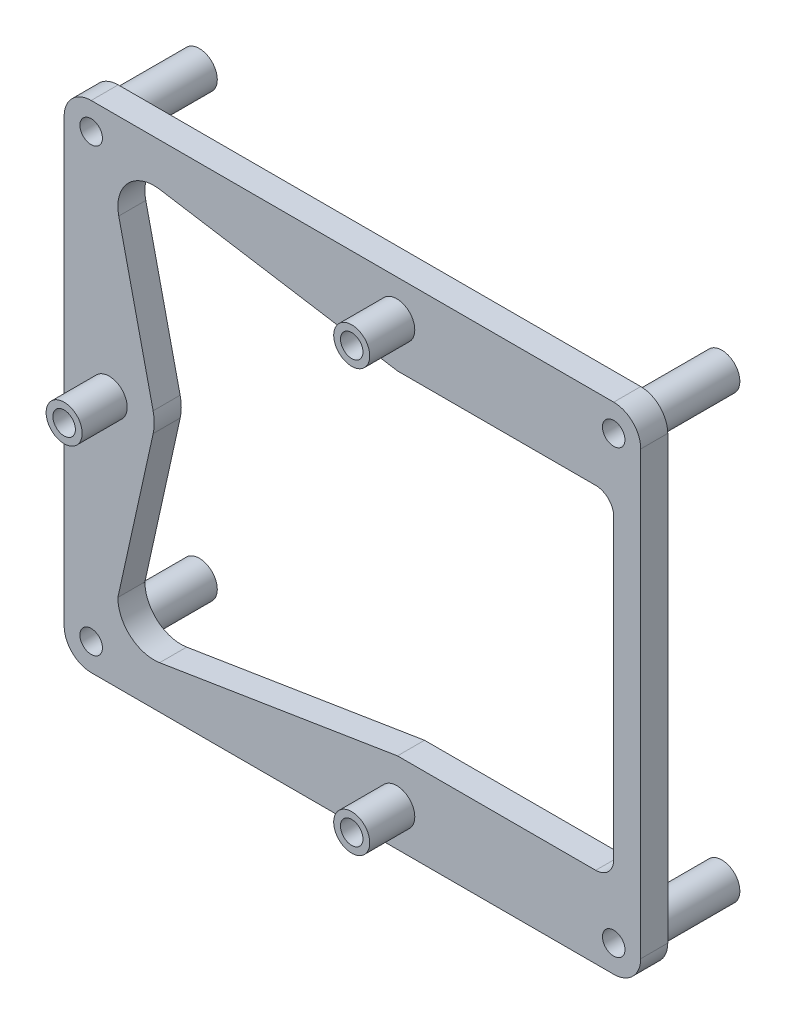
SolidWorks part; units mm, degrees
ref_plane "Alzado" through (0, 0, 0) normal (0, 0, 1) x (1, 0, 0)
ref_plane "Planta" through (0, 0, 0) normal (0, 1, 0) x (1, 0, 0)
ref_plane "Vista lateral" through (0, 0, 0) normal (1, 0, 0) x (0, 0, -1)
sketch "Croquis1" plane through (0, 0, 0) normal (0, 0, 1) x (1, 0, 0)
  line L1 (-36.2308, 25.8462) -> (21.7692, 25.8462)
  line L2 (-39.2308, 22.8462) -> (-39.2308, -26.1538)
  line L3 (-36.2308, -29.1538) -> (21.7692, -29.1538)
  line L4 (24.7692, 22.8462) -> (24.7692, -26.5057)
  arc A4 (-36.2308, 25.8462) -> (-39.2308, 22.8462) centre (-36.2308, 22.8462) ccw
  arc A5 (24.7692, 22.8462) -> (21.7692, 25.8462) centre (21.7692, 22.8462) ccw
  arc A6 (21.7692, -29.1538) -> (24.7692, -26.1538) centre (21.7692, -26.1538) ccw
  arc A7 (-39.2308, -26.1538) -> (-36.2308, -29.1538) centre (-36.2308, -26.1538) ccw
  arc A8 (-36.2308, 25.8462) -> (-39.2308, 22.8462) centre (-36.2308, 22.8462) ccw
  arc A9 (24.7692, 22.8462) -> (21.7692, 25.8462) centre (21.7692, 22.8462) ccw
  arc A10 (-39.2308, -26.1538) -> (-36.2308, -29.1538) centre (-36.2308, -26.1538) ccw
  arc A11 (21.7692, -29.1538) -> (24.7692, -26.1538) centre (21.7692, -26.1538) ccw
  point P35 (0, 0)
  point P36 (-7.2308, 20.5875)
  point P37 (0, 20.5875)
  point P38 (0, 0)
extrude "Saliente-Extruir2" add sketch "Croquis1" along normal blind 3 contours L2 A7 L3 A6 L4 A5 L1 A4
sketch "Croquis2" plane through (0, 0, 0) normal (0, 0, -1) x (-1, 0, 0)
  circle A1 centre (-21.7692, 22.8462) radius 1.25
  circle A3 centre (36.2308, 22.8462) radius 1.25
  circle A5 centre (36.2308, -26.1538) radius 1.25
  circle A7 centre (-21.7692, -26.1538) radius 1.25
  point P7 (36.414, 22.8462)
  point P11 (36.414, -26.8244)
  point P15 (-21.7692, -26.8244)
  point P16 (0, 0)
  point P17 (0, 0)
  point P18 (0, 0)
  point P19 (0, 0)
  point P20 (0, 0)
  point P21 (0, 0)
  dimension "D1" = 2.5
  dimension "D3" = 2.5
  dimension "D5" = 2.5
  dimension "D7" = 2.5
  dimension "D9" = 58
  dimension "D10" = 49
extrude "Cortar-Extruir4" cut sketch "Croquis2" against normal blind 5
sketch "Croquis6" plane through (0, 0, 0) normal (0, 0, -1) x (-1, 0, 0)
  circle A0 centre (-21.7692, 22.8462) radius 2
  circle A1 centre (36.2308, 22.8462) radius 2
  circle A2 centre (36.2308, -26.1538) radius 2
  circle A3 centre (-21.7692, -26.1538) radius 2
  circle A4 centre (-21.7692, 22.8462) radius 1.25
  circle A5 centre (36.2308, 22.8462) radius 1.25
  circle A6 centre (36.2308, -26.1538) radius 1.25
  circle A7 centre (-21.7692, -26.1538) radius 1.25
  dimension "D1" = 4
  dimension "D2" = 4
  dimension "D3" = 4
  dimension "D4" = 4
  dimension "D5" = 2.5
  dimension "D6" = 2.5
extrude "Saliente-Extruir5" add sketch "Croquis6" along normal blind 9
sketch "Croquis4" plane through (0, 0, 3) normal (0, 0, 1) x (1, 0, 0)
  line L0 (-39.2308, 22.8462) -> (-39.2308, -26.1538) construction
  line L1 (-36.2308, 25.8462) -> (21.7692, 25.8462) construction
  circle A0 centre (-2.3108, 21.7462) radius 1.25
  circle A1 centre (-2.3108, -25.0538) radius 1.25
  circle A2 centre (-34.2308, -1.6538) radius 1.25
  circle A3 centre (-34.2308, -1.6538) radius 2
  circle A4 centre (-2.3108, 21.7462) radius 2
  circle A5 centre (-2.3108, -25.0538) radius 2
  point P9 (0, 21.5438)
  point P10 (0, 0)
  point P11 (-34.8352, -1.7286)
  dimension "D1" = 2.5
  dimension "D2" = 2.5
  dimension "D3" = 2.5
  dimension "D4" = 4
  dimension "D5" = 4
  dimension "D6" = 4
  dimension "D10" = 5
  dimension "D11" = 4.1
  dimension "D7" = 31.92
  dimension "D8" = 46.8
  dimension "D9" = 23.4
extrude "Saliente-Extruir4" add sketch "Croquis4" along normal blind 5
sketch "Croquis5" plane through (0, 0, 3) normal (0, 0, 1) x (1, 0, 0)
  line L1 (-2.2308, 16.8462) -> (21.7692, 16.8462)
  line L3 (-2.2308, -20.1538) -> (21.7692, -20.1538)
  line L4 (21.7692, 16.8462) -> (21.7692, -20.1538)
  line L10 (-33.2675, -20.4487) -> (-29.3488, -2.7338)
  line L11 (-29.3546, -0.548) -> (-33.1684, 16.2689)
  line L12 (-2.2308, 16.8462) -> (-28.6308, 21.1026)
  line L13 (-2.2308, -20.1538) -> (-28.6326, -24.398)
  arc A0 (-32.8943, -18.7616) -> (-28.6326, -24.398) centre (-29.2675, -20.4487) ccw
  arc A1 (-28.6308, 21.1026) -> (-33.1684, 16.2689) centre (-29.2675, 17.1536) ccw
  arc A2 (-29.3488, -2.7338) -> (-29.3546, -0.548) centre (-34.2308, -1.6538) ccw
  point P4 (-29.2308, -1.6538)
  point P5 (-29.406, -2.9659)
  point P8 (0, 0)
  dimension "D5" = 8
  dimension "D6" = 8
  dimension "D2" = 5
  dimension "D3" = 26.4018
  dimension "D4" = 26.4
  dimension "D7" = 24
extrude "Cortar-Extruir5" cut sketch "Croquis5" against normal blind 7 contours A2 L10 A0 L13 L3 L4 L1 L12 A1 L11
fillet "Redondeo1" radius 2 2 edges at (21.7692, -20.1538, 1.5) (21.7692, 16.8462, 1.5)
